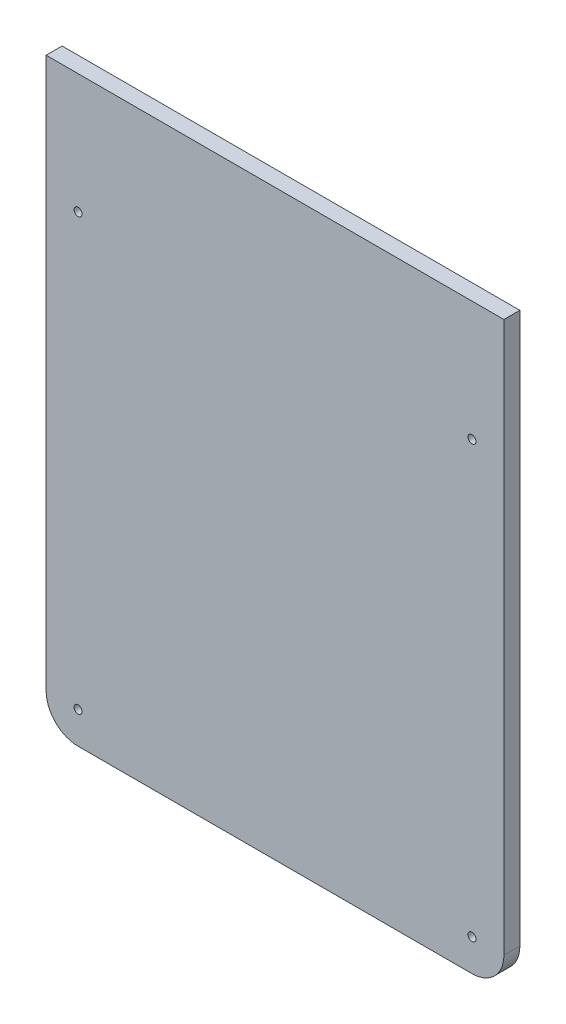
SolidWorks part; units mm, degrees
material "Beech"
ref_plane "Front Plane" through (0, 0, 0) normal (0, 0, 1) x (1, 0, 0)
ref_plane "Top Plane" through (0, 0, 0) normal (0, 1, 0) x (1, 0, 0)
ref_plane "Right Plane" through (0, 0, 0) normal (1, 0, 0) x (0, 0, -1)
sketch "Sketch1" plane through (0, 0, 0) normal (0, 0, 1) x (1, 0, 0)
  line L0 (-19.05, 903.0272) -> (-19.05, 155.124) construction
  line L1 (163.1, 903.0272) -> (163.1, 155.124) construction
  line L2 (-19.05, 903.0272) -> (163.1, 903.0272)
  line L3 (0, 903.0272) -> (19.05, 903.0272) construction
  line L4 (-6.35, 671.2522) -> (150.4, 671.2522) construction
  line L5 (163.1, 683.9522) -> (163.1, 855.4022) construction
  line L6 (-6.35, 671.2522) -> (150.4, 671.2522)
  line L7 (163.1, 683.9522) -> (163.1, 903.0272)
  line L10 (-19.05, 903.0272) -> (-19.05, 683.9522)
  arc A0 (-19.05, 683.9522) -> (-6.35, 671.2522) centre (-6.35, 683.9522) ccw construction
  arc A1 (150.4, 671.2522) -> (163.1, 683.9522) centre (150.4, 683.9522) ccw construction
  arc A2 (-19.05, 683.9522) -> (-6.35, 671.2522) centre (-6.35, 683.9522) ccw
  arc A3 (150.4, 671.2522) -> (163.1, 683.9522) centre (150.4, 683.9522) ccw
extrude "Boss-Extrude1" add sketch "Sketch1" along normal blind 6.35
hole_wizard "Hole1" positions "Sketch2" profile "Sketch3" legacy
sketch "Sketch2" plane through (72.025, -422.2598, 19.05) normal (0, 0, 1) x (1, 0, 0)
  point P0 (-78.375, 1277.6619)
  point P3 (-78.375, 1106.2119)
  point P6 (78.375, 1106.2119)
  point P9 (78.375, 1277.6619)
sketch "Sketch3" plane through (-6.35, 855.4022, 19.05) normal (1, 0, 0) x (0, -1, 0)
  line L0 (0, 0) -> (0, 32.7039)
  line L1 (0, 32.7039) -> (1.5875, 31.75)
  line L2 (1.5875, 31.75) -> (1.5875, 4.0177)
  line L3 (1.5875, 4.0177) -> (5.08, 0)
  line L4 (5.08, 0) -> (0, 0)
  line L5 (0, -14.3089) -> (0, 102.4216) construction
  line L6 (0, 32.7039) -> (-1.5875, 31.75) construction
  line L7 (-1.5875, 4.0177) -> (-5.08, 0) construction
  dimension "Diameter" = 3.175
  dimension "Depth" = 31.75
  dimension "C-Sink Diameter" = 10.16
  dimension "C-Sink Angle" = 82
  dimension "Drill Angle" = 118
